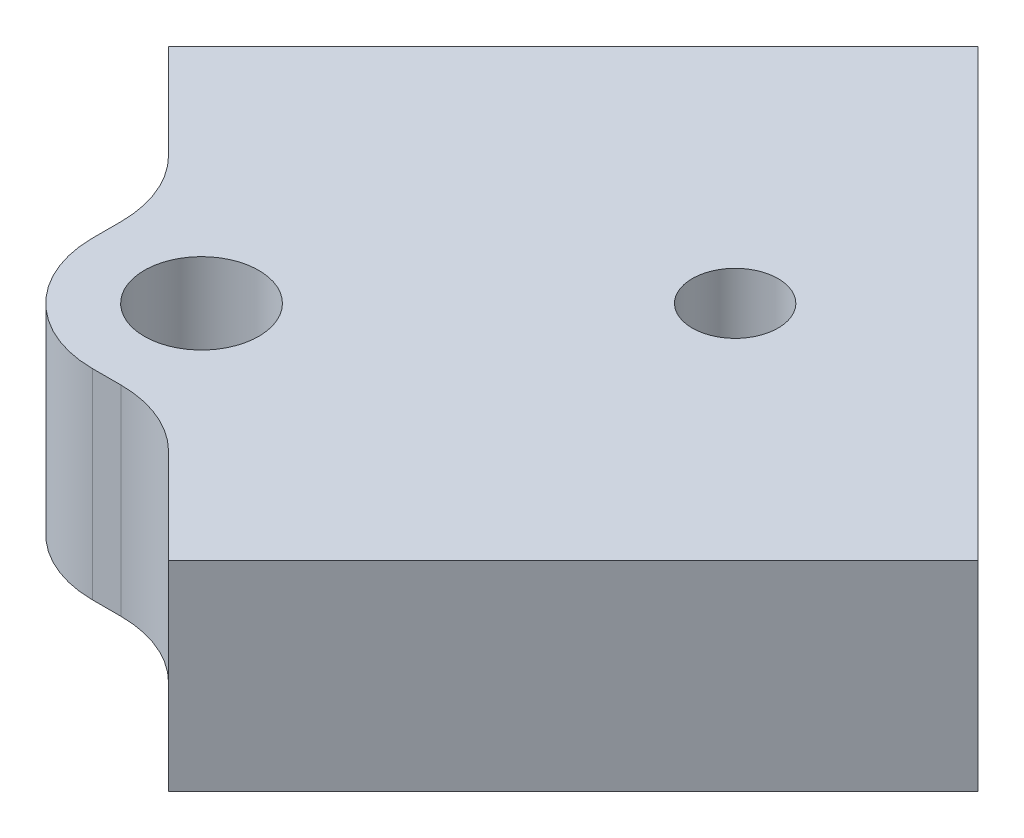
SolidWorks part; units mm, degrees
ref_plane "Ebene vorne" through (0, 0, 0) normal (0, 0, 1) x (1, 0, 0)
ref_plane "Ebene oben" through (0, 0, 0) normal (0, 1, 0) x (1, 0, 0)
ref_plane "Ebene rechts" through (0, 0, 0) normal (1, 0, 0) x (0, 0, -1)
sketch "Skizze1" plane through (0, 0, 0) normal (0, 1, 0) x (1, 0, 0)
  line L1 (0, -3.95) -> (1, -3.95)
  line L3 (0, 0) -> (50000, 0) construction
  line L4 (0, 0) -> (35355.3391, 35355.3391) construction
  line L8 (-3.95, 0) -> (-3.95, 1)
  line L10 (-8.4247, 7.1316) -> (-5.1216, 3.8284)
  line L11 (-8.4247, 7.1316) -> (5.7174, 21.2737)
  line L12 (3.8284, -5.1216) -> (7.1316, -8.4247)
  line L13 (5.7174, 21.2737) -> (21.2737, 5.7174)
  line L14 (21.2737, 5.7174) -> (7.1316, -8.4247)
  arc A0 (-3.95, 0) -> (0, -3.95) centre (0, 0) ccw
  arc A1 (3.8284, -5.1216) -> (1, -3.95) centre (1, -7.95) ccw
  arc A2 (-3.95, 1) -> (-5.1216, 3.8284) centre (-7.95, 1) ccw
  dimension "D2" = 7.9
  dimension "D7" = 8
  dimension "D1" = 1
  dimension "D3" = 22
  dimension "D4" = 45
  dimension "D5" = 20
  dimension "D8" = 1
extrude "Aufsatz-Linear austragen1" add sketch "Skizze1" along normal blind 7
hole_wizard "Ø4.0 (4) Durchmesser Bohrung1" positions "Skizze2" profile "Skizze3" hole size "Ø4.0" standard "ISO" end condition through all
sketch "Skizze2" plane through (0, 7, 0) normal (0, 1, 0) x (1, 0, 0)
  line L1 (0, 0) -> (-50000, 0) construction
  line L2 (0, 0) -> (-35355.3391, -35355.3391) construction
  point P9 (-0.0707, -0.0707)
  dimension "D1" = 45
  dimension "D2" = 0.1
sketch "Skizze3" plane through (-0.0707, 7, 0.0707) normal (1, 0, 0) x (0, 0, 1)
  line L0 (0, 0) -> (0, 7)
  line L1 (0, 7) -> (2, 7)
  line L2 (2, 7) -> (2, 0)
  line L5 (2, 0) -> (0, 0)
  line L11 (0, -6.35) -> (0, 107.95) construction
  dimension "Bohrerdurchmesser" = 4
  dimension "Bohrungstiefe" = 7
hole_wizard "Ø3.0 (3) Durchmesser Bohrung1" positions "Skizze4" profile "Skizze5" hole size "Ø3.0" standard "ISO" end condition through all
sketch "Skizze4" plane through (0, 7, 0) normal (0, 1, 0) x (1, 0, 0)
  line L0 (0, 0) -> (-50000, 0) construction
  line L1 (0, 0) -> (35355.3391, 35355.3391) construction
  line L2 (21.2737, 5.7174) -> (5.7174, 21.2737) construction
  point P7 (9.2529, 9.2529)
  dimension "D1" = 45
  dimension "D2" = 6
sketch "Skizze5" plane through (9.2529, 7, -9.2529) normal (1, 0, 0) x (0, 0, 1)
  line L0 (0, 0) -> (0, 7)
  line L1 (0, 7) -> (1.5, 7)
  line L2 (1.5, 7) -> (1.5, 0)
  line L5 (1.5, 0) -> (0, 0)
  line L11 (0, -6.35) -> (0, 107.95) construction
  dimension "Bohrerdurchmesser" = 3
  dimension "Bohrungstiefe" = 7
